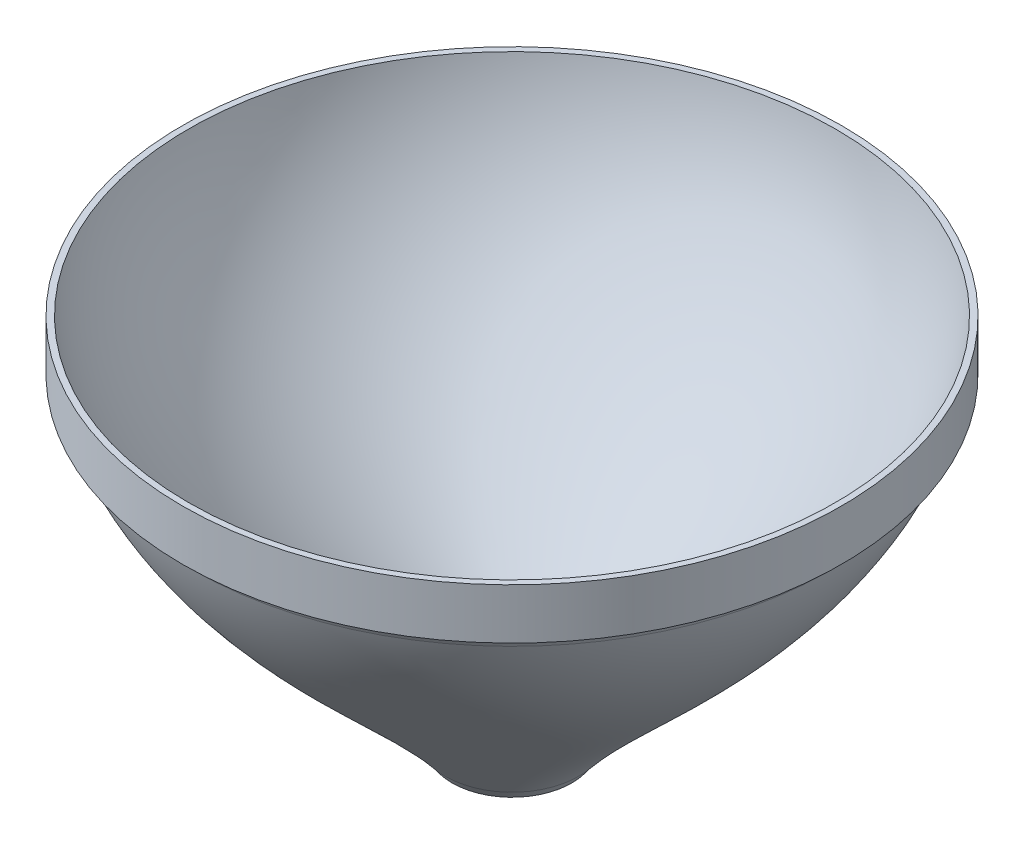
SolidWorks part; units mm, degrees
ref_plane "Płaszczyzna przednia" through (0, 0, 0) normal (0, 0, 1) x (1, 0, 0)
ref_plane "Płaszczyzna górna" through (0, 0, 0) normal (0, 1, 0) x (1, 0, 0)
ref_plane "Płaszczyzna prawa" through (0, 0, 0) normal (1, 0, 0) x (0, 0, -1)
sketch "Sketch1" plane through (0, 0, 0) normal (0, 0, 1) x (1, 0, 0)
  line L0 (-20.1658, 177.6565) -> (-20.1658, 45.3185)
  line L1 (-20.1658, 45.3185) -> (-18.1658, 45.3185)
  line L2 (-18.1658, 45.3185) -> (-18.1658, 175.6565)
  line L3 (-18.1658, 175.6565) -> (-4.1658, 175.6565)
  line L4 (-4.1658, 175.6565) -> (-4.1658, 174.0528)
  line L5 (-4.1658, 174.0528) -> (-2.6658, 174.0528)
  line L6 (-2.6658, 174.0528) -> (-2.6658, 175.6565)
  line L8 (24.8342, 176.1565) -> (24.8342, 177.6565)
  line L10 (-2.6658, 177.1565) -> (-2.6658, 182.6565)
  line L11 (-2.6658, 182.6565) -> (-4.1658, 182.6565)
  line L12 (-4.1658, 182.6565) -> (-4.1658, 177.6565)
  line L13 (-4.1658, 177.6565) -> (-20.1658, 177.6565)
  line L15 (24.8342, 148.4714) -> (24.8342, -40.5547) construction
  line L16 (-4.1658, 177.6565) -> (-4.1658, 175.6565)
  line L17 (-3.9845, 53.8719) -> (56.7742, 96.4156)
  line L21 (56.7742, 96.4156) -> (56.7742, 93.974)
  line L22 (56.7742, 93.974) -> (-3.4255, 51.8217)
  line L26 (18.8342, 85.6565) -> (16.872, 85.6565)
  line L30 (-18.1658, 128.7465) -> (-18.9658, 128.7465)
  line L32 (-18.1658, 135.4565) -> (-18.9658, 135.4565)
  line L33 (-18.9658, 135.4565) -> (-18.9658, 128.7465)
  line L34 (-18.1658, 128.5465) -> (-19.1658, 128.5465)
  line L35 (-19.1658, 128.5465) -> (-19.1658, 135.6565)
  line L36 (-19.1658, 135.6565) -> (-18.1658, 135.6565)
  line L37 (-2.6658, 177.1565) -> (-2.6658, 175.6565)
  line L38 (-17.5576, 127.3754) -> (-17.5576, 127.3754)
  line L39 (-17.5576, 127.3754) -> (-17.5576, 127.3754)
  line L40 (-17.5576, 127.3754) -> (-17.5576, 127.3754)
  line L41 (15.9828, 86.8645) -> (16.872, 85.6565)
  line L42 (-17.5576, 127.3754) -> (-18.1658, 128.7465)
  line L43 (15.9828, 86.8645) -> (15.9828, 86.8645) construction
  spline S0 degree 3 poles (-18.1658, 135.4565) (-14.4546, 112.7695) (7.6229, 100.7425) (18.8342, 85.6565) knots 0 0 0 0 1 1 1 1
  spline S1 degree 1 poles (-17.5576, 127.3754) (15.9828, 86.8645) knots 0 0 1 1 construction
  spline S2 degree 3 poles (-17.5576, 127.3754) (-17.1493, 126.2825) (-16.2379, 124.1197) (-14.13, 120.0244) (-9.7541, 113.3263) (-3.6348, 106.5855) (2.7798, 100.3454) (7.5389, 95.8197) (11.2889, 92.1067) (14.0705, 89.1159) (15.3533, 87.63) (15.9828, 86.8645) knots 0.117145 0.117145 0.117145 0.117145 0.169312 0.221479 0.325814 0.534482 0.638817 0.743151 0.847485 0.899652 0.95182 0.95182 0.95182 0.95182
  dimension "D1" = 2
  dimension "D3" = 2
  dimension "D4" = 5
  dimension "D5" = 1.5
  dimension "D6" = 45
  dimension "D2" = 0.2
  dimension "D10" = 0.2
  dimension "D11" = 0.2
  dimension "D7" = 6
  dimension "D12" = 7.11
  dimension "D8" = 1
  dimension "D13" = 40
  dimension "D14" = 90
  dimension "D9" = 1.5
revolve "Revolve1" add sketch "Sketch1" angle 360 about L15
equation "\"outerdiameter\"= 45"
equation "\"D6@Sketch1\"=\"outerdiameter\""
equation "\"wallthick\"= 2"
equation "\"D1@Sketch1\"=\"wallthick\""
equation "\"D3@Sketch1\"=\"wallthick\""
